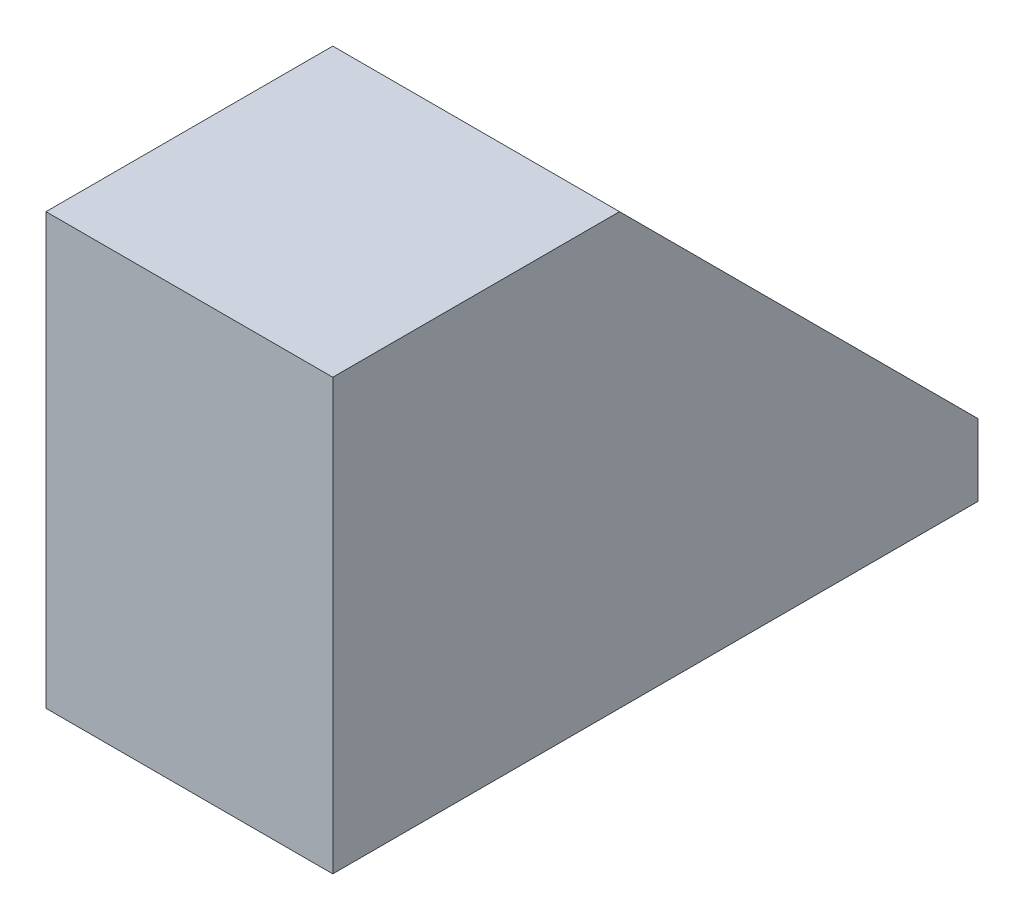
SolidWorks part; units mm, degrees
ref_plane "Alzado" through (0, 0, 0) normal (0, 0, 1) x (1, 0, 0)
ref_plane "Planta" through (0, 0, 0) normal (0, 1, 0) x (1, 0, 0)
ref_plane "Vista lateral" through (0, 0, 0) normal (1, 0, 0) x (0, 0, -1)
sketch "Croquis4" plane through (0, 0, 0) normal (1, 0, 0) x (0, 0, -1)
  line L0 (-5, 30) -> (45, -20)
  line L1 (-45, -30) -> (45, -30)
  line L2 (-45, -30) -> (-45, 30)
  line L3 (-45, 30) -> (-5, 30)
  line L4 (45, -30) -> (45, -20)
  line L5 (-45, -30) -> (45, 30) construction
  line L6 (-45, 30) -> (45, -30) construction
  point P0 (0, 0)
  dimension "D1" = 60
  dimension "D2" = 90
extrude "Saliente-Extruir3" add sketch "Croquis4" along normal blind 40
sketch "Croquis6" plane through (0, 12.5, -12.5) normal (0, 0.7071, -0.7071) x (-1, 0, 0)
  line L0 (-16.6401, 10.551) -> (-18.3776, -30.8279)
  text T0 "SOLIDWORKS\r\n2026" font "Century Gothic" height 5
